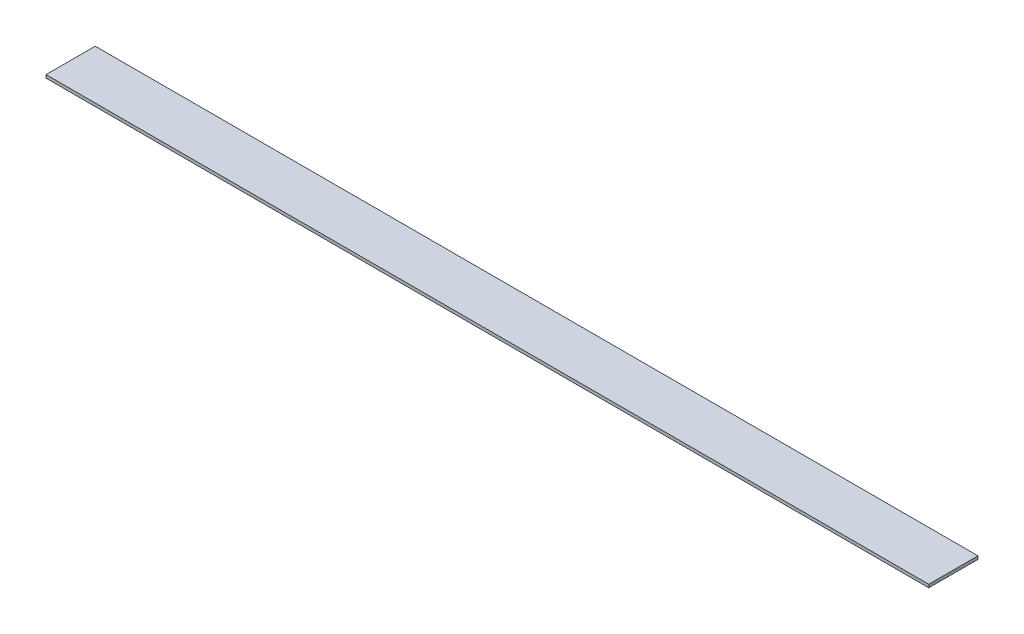
SolidWorks part; units mm, degrees
ref_plane "Front Plane" through (0, 0, 0) normal (0, 0, 1) x (1, 0, 0)
ref_plane "Top Plane" through (0, 0, 0) normal (0, 1, 0) x (1, 0, 0)
ref_plane "Right Plane" through (0, 0, 0) normal (1, 0, 0) x (0, 0, -1)
sketch "Sketch1" plane through (0, 0, 0) normal (0, 1, 0) x (1, 0, 0)
  line L1 (0, 0) -> (910.88, 0)
  line L2 (0, 0) -> (0, 50.8)
  line L3 (0, 50.8) -> (910.88, 50.8)
  line L4 (910.88, 0) -> (910.88, 50.8)
  dimension "D1" = 50.8
  dimension "D2" = 910.88
extrude "Boss-Extrude1" add sketch "Sketch1" along normal blind 3.175
